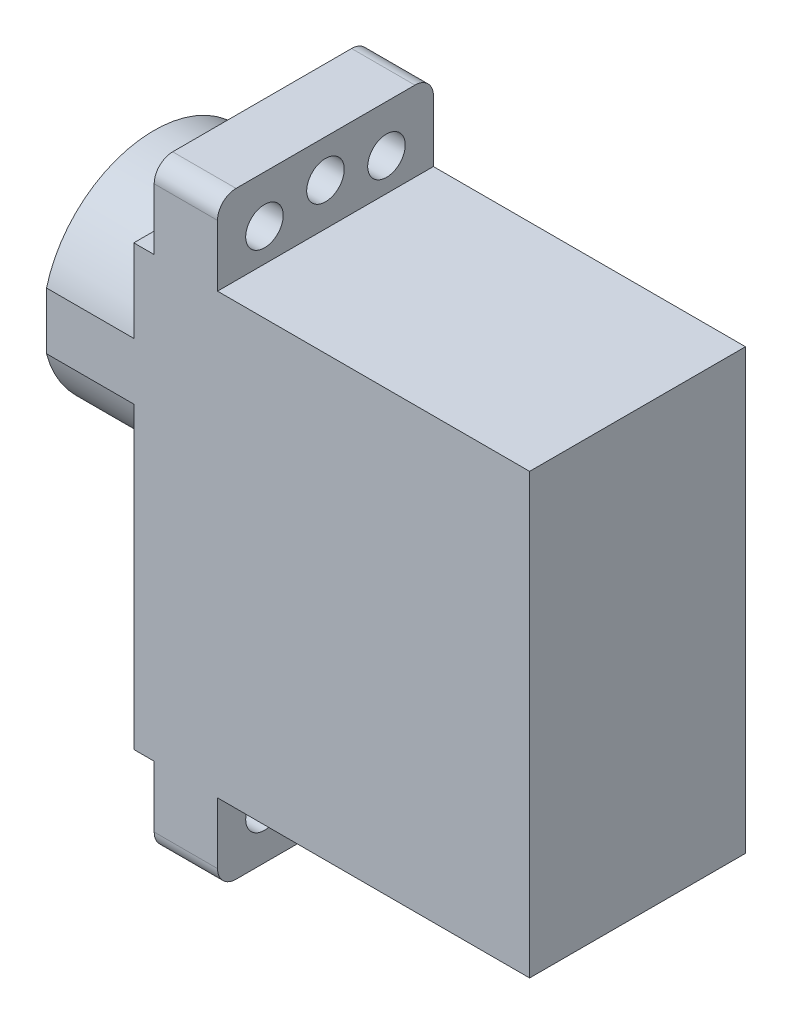
SolidWorks part; units mm, degrees
material "Acier non allié"
ref_plane "Plan de face" through (0, 0, 0) normal (0, 0, 1) x (1, 0, 0)
ref_plane "Plan de dessus" through (0, 0, 0) normal (0, 1, 0) x (1, 0, 0)
ref_plane "Plan de droite" through (0, 0, 0) normal (1, 0, 0) x (0, 0, -1)
sketch "Esquisse1" plane through (0, 0, 0) normal (0, 0, 1) x (1, 0, 0)
  line L1 (0, 0) -> (21.4235, 0)
  line L2 (0, 0) -> (0, 23.749)
  line L3 (0, 23.749) -> (21.4235, 23.749)
  line L4 (21.4235, 0) -> (21.4235, 23.749)
  dimension "D1" = 23.749
  dimension "D2" = 21.4235
extrude "Boss.-Extru.1" add sketch "Esquisse1" along normal blind 11.684
sketch "Esquisse2" plane through (0, 0, 0) normal (0, -1, 0) x (1, 0, 0)
  line L0 (0, 0) -> (21.4235, 0) construction
  line L1 (1.1035, 0) -> (4.5325, 0)
  line L2 (1.1035, 0) -> (1.1035, 11.684)
  line L3 (1.1035, 11.684) -> (4.5325, 11.684)
  line L4 (4.5325, 0) -> (4.5325, 11.684)
  line L5 (0, 11.684) -> (21.4235, 11.684) construction
  line L6 (0, 11.684) -> (0, 0) construction
  dimension "D1" = 3.429
  dimension "D2" = 1.1035
extrude "Boss.-Extru.2" add sketch "Esquisse2" along normal blind 4.318 and the other way blind 28.067
sketch "Esquisse4" plane through (1.1035, 0, 0) normal (-1, 0, 0) x (0, 0, 1)
  line L0 (16.7403, 11.8745) -> (-7.2535, 11.8745) construction
  line L1 (0, 0) -> (0, -4.318) construction
  line L2 (11.684, 23.749) -> (0, 23.749) construction
  line L3 (11.684, 0) -> (0, 0) construction
  line L4 (5.842, -13.135) -> (5.842, 35.4319) construction
  line L5 (11.684, 28.067) -> (11.684, 23.749) construction
  line L6 (0, 28.067) -> (0, 23.749) construction
  circle A0 centre (2.54, -1.778) radius 1.016
  circle A1 centre (5.842, -2.286) radius 1.016
  circle A2 centre (9.144, -1.778) radius 1.016
  circle A3 centre (9.144, 25.527) radius 1.016
  circle A4 centre (5.842, 26.035) radius 1.016
  circle A5 centre (2.54, 25.527) radius 1.016
  dimension "D3" = 2.032
  dimension "D1" = 27.305
  dimension "D2" = 28.321
  dimension "D4" = 2.54
  dimension "D5" = 6.604
extrude "Enlèv. mat.-Extru.1" cut sketch "Esquisse4" against normal up to next
fillet "Congé1" radius 1 4 edges at (2.818, 28.067, 11.684) (2.818, 28.067, 0) (2.818, -4.318, 11.684) (2.818, -4.318, 0)
sketch "Esquisse5" plane through (0, 0, 0) normal (-1, 0, 0) x (0, 0, 1)
  line L0 (11.684, 23.749) -> (0, 23.749) construction
  circle A0 centre (5.8646, 17.7292) radius 6.0198
  dimension "D2" = 12.0396
  dimension "D1" = 6.0198
extrude "Boss.-Extru.3" add sketch "Esquisse5" along normal blind 4.7244
sketch "Esquisse6" plane through (0, 0, 0) normal (-1, 0, 0) x (0, 0, 1)
  line L0 (5.842, -6.1852) -> (5.842, 31.1511) construction
  line L1 (11.684, 0) -> (12.684, 0)
  line L2 (11.684, 0) -> (11.684, 23.749)
  line L3 (11.684, 23.749) -> (12.684, 23.749)
  line L4 (12.684, 0) -> (12.684, 23.749)
  line L5 (0, 16.3712) -> (0, 0) construction
  line L6 (0, 23.749) -> (-1, 23.749)
  line L7 (-1, 0) -> (-1, 23.749)
  line L8 (0, 0) -> (0, 23.749)
  line L9 (0, 0) -> (-1, 0)
  dimension "D1" = 1
extrude "Enlèv. mat.-Extru.2" cut sketch "Esquisse6" along normal blind 4.7244
